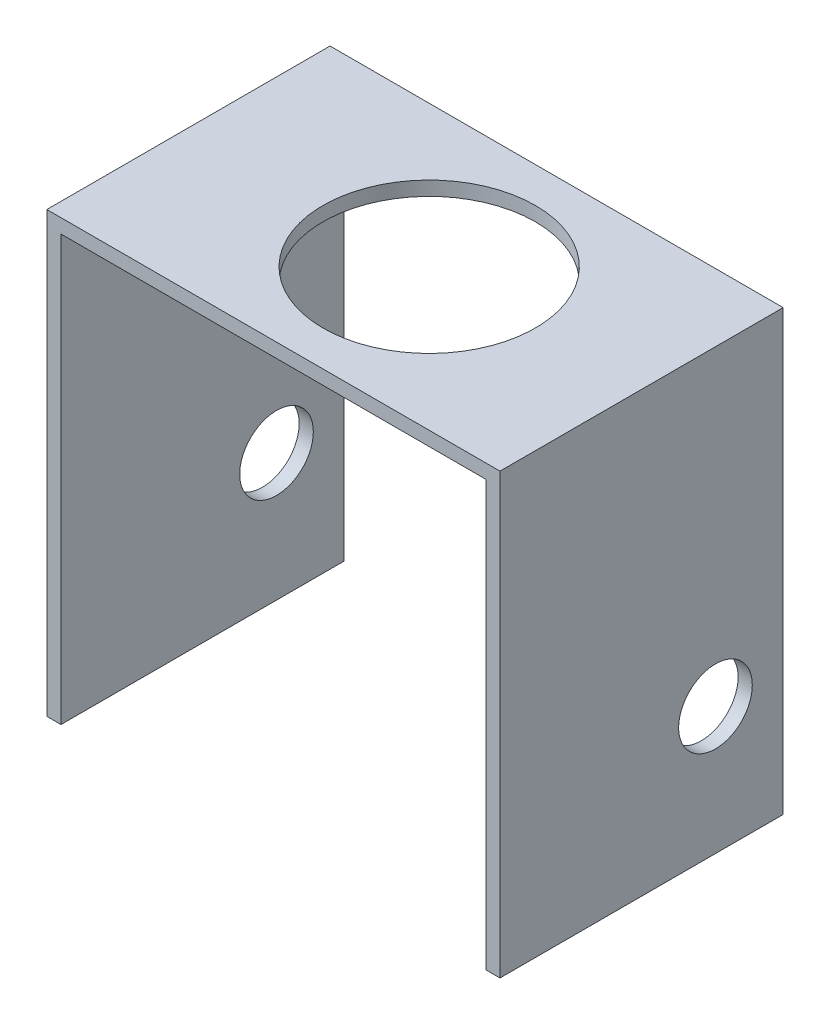
SolidWorks part; units mm, degrees
ref_plane "Front Plane" through (0, 0, 0) normal (0, 0, 1) x (1, 0, 0)
ref_plane "Top Plane" through (0, 0, 0) normal (0, 1, 0) x (1, 0, 0)
ref_plane "Right Plane" through (0, 0, 0) normal (1, 0, 0) x (0, 0, -1)
sketch "Sketch10" plane through (0, 0, 0) normal (0, 0, 1) x (1, 0, 0)
  line L1 (-18.4297, 15.077) -> (-17.4297, 15.077)
  line L2 (-18.4297, 15.077) -> (-18.4297, -14.923)
  line L3 (-18.4297, -14.923) -> (-17.4297, -14.923)
  line L4 (-17.4297, 15.077) -> (-17.4297, -14.923)
  line L5 (-18.4297, 15.077) -> (13.5703, 15.077)
  line L6 (-18.4297, 15.077) -> (-18.4297, 16.077)
  line L7 (-18.4297, 16.077) -> (13.5703, 16.077)
  line L8 (13.5703, 15.077) -> (13.5703, 16.077)
  line L9 (13.5703, 15.077) -> (12.5703, 15.077)
  line L10 (13.5703, 15.077) -> (13.5703, -14.923)
  line L11 (13.5703, -14.923) -> (12.5703, -14.923)
  line L12 (12.5703, 15.077) -> (12.5703, -14.923)
  dimension "D1" = 32
  dimension "D2" = 30
  dimension "D3" = 1
  dimension "D4" = 1
  dimension "D5" = 30
  dimension "D6" = 1
extrude "Boss-Extrude1" add sketch "Sketch10" along normal blind 20 contours L4 L1 L2 L3 | L5 L12 L11 L10 | L5 L8 L7 L6 L1
sketch "Sketch11" plane through (13.5703, 0, 0) normal (1, 0, 0) x (0, 0, -1)
  line L0 (-20, 16.077) -> (0, 16.077) construction
  circle A0 centre (-4.7803, -5.923) radius 2.6
  dimension "D1" = 22
extrude "Cut-Extrude1" cut sketch "Sketch11" against normal through all
sketch "Sketch12" plane through (0, 16.077, 0) normal (0, 1, 0) x (1, 0, 0)
  line L3 (13.5703, -20) -> (13.5703, 0) construction
  circle A0 centre (-1.4297, -10) radius 7.5
  point P6 (6.2106, -8.7366)
  dimension "D1" = 15
  dimension "D2" = 15
extrude "Cut-Extrude2" cut sketch "Sketch12" against normal through all
